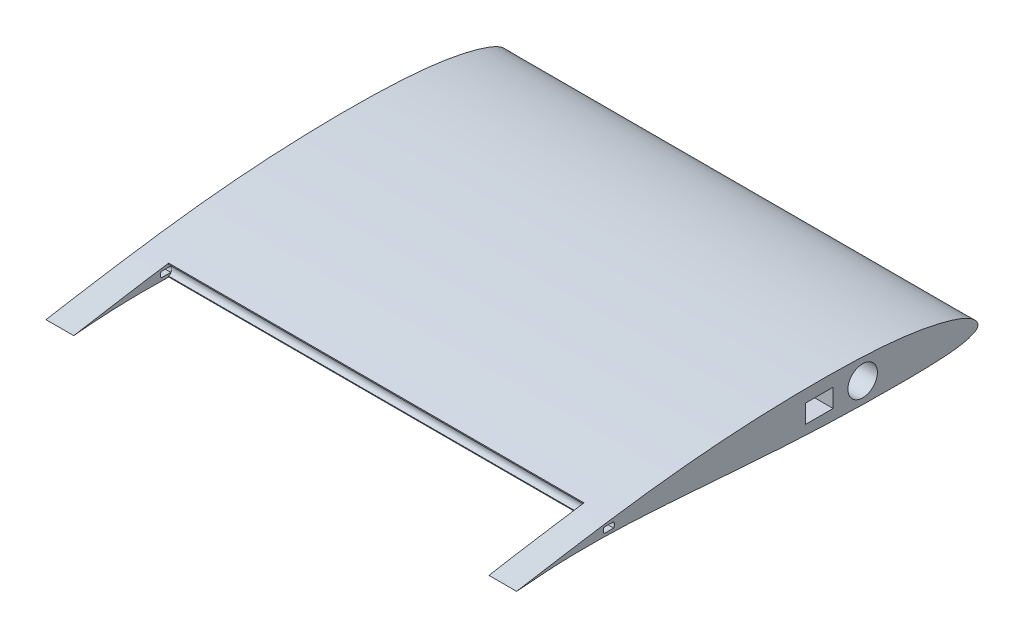
SolidWorks part; units mm, degrees
material "Foam"
ref_plane "Piano frontale" through (0, 0, 0) normal (0, 0, 1) x (1, 0, 0)
ref_plane "Piano superiore" through (0, 0, 0) normal (0, 1, 0) x (1, 0, 0)
ref_plane "Piano destro" through (0, 0, 0) normal (1, 0, 0) x (0, 0, -1)
curve "Curva1"
  spline degree 3 poles (0, 0.1724, 248.285) (0, -0.053, 250.4273) (0, 0.2462, 248.3284) (0, 0.5529, 246.6445) (0, 1.2459, 242.6221) (0, 2.0989, 237.7464) (0, 3.1818, 231.3634) (0, 4.2933, 223.9772) (0, 5.7312, 215.5604) (0, 7.1315, 206.3004) (0, 8.6324, 196.1631) (0, 10.1162, 185.3524) (0, 11.5493, 173.9891) (0, 12.8816, 162.1914) (0, 14.0593, 150.0724) (0, 15.0523, 137.7438) (0, 15.8256, 125.3116) (0, 16.3834, 112.8888) (0, 16.7267, 100.597) (0, 16.8648, 88.5669) (0, 16.792, 76.9314) (0, 16.4941, 65.8165) (0, 15.9609, 55.3329) (0, 15.1594, 45.573) (0, 14.0978, 36.6074) (0, 12.7884, 28.4972) (0, 11.2839, 21.2988) (0, 9.6413, 15.0749) (0, 7.9136, 9.8809) (0, 6.1182, 5.7699) (0, 4.2384, 2.7289) (0, 2.3057, 0.8126) (0, 0.7927, 0.0312) (0, -0.4105, -0.0213) (0, -1.7115, 0.4949) (0, -2.8658, 2.6253) (0, -4.0404, 5.6977) (0, -4.9287, 10.0719) (0, -5.5974, 15.6262) (0, -6.0122, 22.4122) (0, -6.265, 30.3619) (0, -6.3814, 39.3972) (0, -6.3554, 49.3987) (0, -6.2185, 60.2453) (0, -5.9476, 71.8018) (0, -5.5368, 83.9408) (0, -4.9386, 96.5461) (0, -4.1527, 109.5201) (0, -3.2196, 122.7671) (0, -2.1909, 136.1764) (0, -1.148, 149.6158) (0, -0.1602, 162.9314) (0, 0.706, 175.9537) (0, 1.3896, 188.4999) (0, 1.8332, 200.3712) (0, 1.9676, 211.3376) (0, 1.8232, 221.1842) (0, 1.4973, 229.6804) (0, 1.0741, 236.8065) (0, 0.6857, 242.1894) (0, 0.3087, 246.5181) (0, 0.1724, 248.285) (0, -0.053, 250.4273) (0, 0.2462, 248.3284) knots -0.014202 -0.006329 -0.001589 0 0.001576 0.006211 0.01368 0.023764 0.036307 0.051658 0.068045 0.086769 0.107053 0.128647 0.151303 0.174786 0.19886 0.223309 0.247929 0.272522 0.296848 0.320648 0.343669 0.365658 0.3864 0.405741 0.423561 0.439779 0.454311 0.467034 0.477831 0.486643 0.493542 0.498786 0.50271 0.50309 0.505896 0.510322 0.516831 0.525521 0.536535 0.549945 0.565696 0.583577 0.603379 0.624844 0.647727 0.671743 0.696673 0.722357 0.748609 0.77521 0.801891 0.828329 0.854175 0.879074 0.902636 0.924421 0.943939 0.960827 0.974827 0.985798 0.993671 0.998411 1 1.001576 1.006211 1.01368 periodic
sketch "Schizzo1" plane through (0, 0, 0) normal (1, 0, 0) x (0, 0, -1)
  line L0 (-250, 0) -> (0.0001, 0.0174) construction
  line L1 (0.0001, 0.0174) -> (-0.0034, 50.0174) construction
  line L2 (-62.4999, 16.3096) -> (-62.4999, -6.155) construction
  line L3 (-200, 8.0593) -> (-200, 1.7757) construction
  line L4 (-93.4999, 10.0773) -> (-78.4999, 10.0773)
  line L5 (-93.4999, 10.0773) -> (-93.4999, 0.0773)
  line L6 (-93.4999, 0.0773) -> (-78.4999, 0.0773)
  line L7 (-78.4999, 10.0773) -> (-78.4999, 0.0773)
  circle A0 centre (-62.4999, 5.0773) radius 8
  arc A1 (-200, 8.0593) -> (-200, 1.7757) centre (-200, 4.9175) cw
  spline S0 degree 3 poles (-248.3284, 0.2462) (-250.4273, -0.053) (-248.285, 0.1724) (-246.5181, 0.3087) (-242.1894, 0.6857) (-236.8065, 1.0741) (-229.6804, 1.4973) (-221.1842, 1.8232) (-211.3376, 1.9676) (-200.3712, 1.8332) (-188.4999, 1.3896) (-175.9537, 0.706) (-162.9314, -0.1602) (-149.6158, -1.148) (-136.1764, -2.1909) (-122.7671, -3.2196) (-109.5201, -4.1527) (-96.5461, -4.9386) (-83.9408, -5.5368) (-71.8018, -5.9476) (-60.2453, -6.2185) (-49.3987, -6.3554) (-39.3972, -6.3814) (-30.3619, -6.265) (-22.4122, -6.0122) (-15.6262, -5.5974) (-10.0719, -4.9287) (-5.6977, -4.0404) (-2.6253, -2.8658) (-0.4949, -1.7115) (0.0213, -0.4105) (-0.0312, 0.7927) (-0.8126, 2.3057) (-2.7289, 4.2384) (-5.7699, 6.1182) (-9.8809, 7.9136) (-15.0749, 9.6413) (-21.2988, 11.2839) (-28.4972, 12.7884) (-36.6074, 14.0978) (-45.573, 15.1594) (-55.3329, 15.9609) (-65.8165, 16.4941) (-76.9314, 16.792) (-88.5669, 16.8648) (-100.597, 16.7267) (-112.8888, 16.3834) (-125.3116, 15.8256) (-137.7438, 15.0523) (-150.0724, 14.0593) (-162.1914, 12.8816) (-173.9891, 11.5493) (-185.3524, 10.1162) (-196.1631, 8.6324) (-206.3004, 7.1315) (-215.5604, 5.7312) (-223.9772, 4.2933) (-231.3634, 3.1818) (-237.7464, 2.0989) (-242.6221, 1.2459) (-246.6445, 0.5529) (-248.3284, 0.2462) (-250.4273, -0.053) (-248.285, 0.1724) knots -0.01368 -0.006211 -0.001576 0 0.001589 0.006329 0.014202 0.025173 0.039173 0.056061 0.075579 0.097364 0.120926 0.145825 0.171671 0.198109 0.22479 0.251391 0.277643 0.303327 0.328257 0.352273 0.375156 0.396621 0.416423 0.434304 0.450055 0.463465 0.474479 0.483169 0.489678 0.494104 0.49691 0.49729 0.501214 0.506458 0.513357 0.522169 0.532966 0.545689 0.560221 0.576439 0.594259 0.6136 0.634342 0.656331 0.679352 0.703152 0.727478 0.752071 0.776691 0.80114 0.825214 0.848697 0.871353 0.892947 0.913231 0.931955 0.948342 0.963693 0.976236 0.98632 0.993789 0.998424 1 1.001589 1.006329 1.014202 only from (-250, 0) to (-250, 0) construction
  spline S1 degree 3 poles (-200, 1.7757) (-196.2415, 1.6788) (-188.276, 1.3774) (-175.9537, 0.706) (-162.9314, -0.1602) (-149.6158, -1.148) (-136.1764, -2.1909) (-122.7671, -3.2196) (-109.5201, -4.1527) (-96.5461, -4.9386) (-83.9408, -5.5368) (-71.8018, -5.9476) (-60.2453, -6.2185) (-49.3987, -6.3554) (-39.3972, -6.3814) (-30.3619, -6.265) (-22.4122, -6.0122) (-15.6262, -5.5974) (-10.0719, -4.9287) (-5.6977, -4.0404) (-2.6253, -2.8658) (-0.4949, -1.7115) (0.0213, -0.4105) (-0.0312, 0.7927) (-0.8126, 2.3057) (-2.7289, 4.2384) (-5.7699, 6.1182) (-9.8809, 7.9136) (-15.0749, 9.6413) (-21.2988, 11.2839) (-28.4972, 12.7884) (-36.6074, 14.0978) (-45.573, 15.1594) (-55.3329, 15.9609) (-65.8165, 16.4941) (-76.9314, 16.792) (-88.5669, 16.8648) (-100.597, 16.7267) (-112.8888, 16.3834) (-125.3116, 15.8256) (-137.7438, 15.0523) (-150.0724, 14.0593) (-162.1914, 12.8816) (-173.9891, 11.5493) (-185.3524, 10.1162) (-193.973, 8.933) (-198.7936, 8.2355) (-200, 8.0593) knots 0.09869 0.09869 0.09869 0.09869 0.120926 0.145825 0.171671 0.198109 0.22479 0.251391 0.277643 0.303327 0.328257 0.352273 0.375156 0.396621 0.416423 0.434304 0.450055 0.463465 0.474479 0.483169 0.489678 0.494104 0.49691 0.49729 0.501214 0.506458 0.513357 0.522169 0.532966 0.545689 0.560221 0.576439 0.594259 0.6136 0.634342 0.656331 0.679352 0.703152 0.727478 0.752071 0.776691 0.80114 0.825214 0.848697 0.871353 0.892947 0.900158 0.900158 0.900158 0.900158
  point P12 (-78.4999, 5.0773)
  dimension "D3" = 16
  dimension "D1" = 50
  dimension "D2" = 62.5
  dimension "D4" = 15
  dimension "D5" = 10
  dimension "D6" = 16
  dimension "D7" = 50
  dimension "D8" = 6.2836
extrude "CorpoFoam" add sketch "Schizzo1" along normal blind 225
sketch "Schizzo2" plane through (225, 0, 0) normal (1, 0, 0) x (0, 0, -1)
  line L0 (-200, 8.0593) -> (-200, 1.7757) construction
  line L1 (-203.5, 8.2775) -> (-198.5, 8.2775)
  line L2 (-203.5, 8.2775) -> (-203.5, 1.7346)
  line L3 (-203.5, 1.7346) -> (-198.5, 1.7346)
  line L4 (-198.5, 8.2775) -> (-198.5, 1.7346)
  arc A0 (-200, 1.7757) -> (-200, 8.0593) centre (-200, 4.9175) ccw construction
  spline S0 degree 3 poles (-248.3284, 0.2462) (-250.4273, -0.053) (-248.285, 0.1724) (-246.5181, 0.3087) (-242.1894, 0.6857) (-236.8065, 1.0741) (-229.6804, 1.4973) (-221.1842, 1.8232) (-211.3376, 1.9676) (-200.3712, 1.8332) (-188.4999, 1.3896) (-175.9537, 0.706) (-162.9314, -0.1602) (-149.6158, -1.148) (-136.1764, -2.1909) (-122.7671, -3.2196) (-109.5201, -4.1527) (-96.5461, -4.9386) (-83.9408, -5.5368) (-71.8018, -5.9476) (-60.2453, -6.2185) (-49.3987, -6.3554) (-39.3972, -6.3814) (-30.3619, -6.265) (-22.4122, -6.0122) (-15.6262, -5.5974) (-10.0719, -4.9287) (-5.6977, -4.0404) (-2.6253, -2.8658) (-0.4949, -1.7115) (0.0213, -0.4105) (-0.0312, 0.7927) (-0.8126, 2.3057) (-2.7289, 4.2384) (-5.7699, 6.1182) (-9.8809, 7.9136) (-15.0749, 9.6413) (-21.2988, 11.2839) (-28.4972, 12.7884) (-36.6074, 14.0978) (-45.573, 15.1594) (-55.3329, 15.9609) (-65.8165, 16.4941) (-76.9314, 16.792) (-88.5669, 16.8648) (-100.597, 16.7267) (-112.8888, 16.3834) (-125.3116, 15.8256) (-137.7438, 15.0523) (-150.0724, 14.0593) (-162.1914, 12.8816) (-173.9891, 11.5493) (-185.3524, 10.1162) (-196.1631, 8.6324) (-206.3004, 7.1315) (-215.5604, 5.7312) (-223.9772, 4.2933) (-231.3634, 3.1818) (-237.7464, 2.0989) (-242.6221, 1.2459) (-246.6445, 0.5529) (-248.3284, 0.2462) (-250.4273, -0.053) (-248.285, 0.1724) knots -0.01368 -0.006211 -0.001576 0 0.001589 0.006329 0.014202 0.025173 0.039173 0.056061 0.075579 0.097364 0.120926 0.145825 0.171671 0.198109 0.22479 0.251391 0.277643 0.303327 0.328257 0.352273 0.375156 0.396621 0.416423 0.434304 0.450055 0.463465 0.474479 0.483169 0.489678 0.494104 0.49691 0.49729 0.501214 0.506458 0.513357 0.522169 0.532966 0.545689 0.560221 0.576439 0.594259 0.6136 0.634342 0.656331 0.679352 0.703152 0.727478 0.752071 0.776691 0.80114 0.825214 0.848697 0.871353 0.892947 0.913231 0.931955 0.948342 0.963693 0.976236 0.98632 0.993789 0.998424 1 1.001589 1.006329 1.014202 only from (-250, 0) to (-250, 0) construction
  dimension "D1" = 5
  dimension "D2" = 1.5
extrude "SmussoPosteriore" cut sketch "Schizzo2" against normal through all
sketch "Schizzo3" plane through (225, 0, 0) normal (1, 0, 0) x (0, 0, -1)
  line L1 (-93.4999, 10.0773) -> (-78.4999, 10.0773)
  line L2 (-93.4999, 10.0773) -> (-93.4999, 0.0773)
  line L3 (-93.4999, 0.0773) -> (-78.4999, 0.0773)
  line L4 (-78.4999, 10.0773) -> (-78.4999, 0.0773)
  circle A0 centre (-62.4999, 5.0773) radius 8
  circle A1 centre (-62.4999, 5.0773) radius 8 construction
  spline S0 degree 3 poles (-248.3284, 0.2462) (-250.4273, -0.053) (-248.285, 0.1724) (-246.5181, 0.3087) (-242.1894, 0.6857) (-236.8065, 1.0741) (-229.6804, 1.4973) (-221.1842, 1.8232) (-211.3376, 1.9676) (-200.3712, 1.8332) (-188.4999, 1.3896) (-175.9537, 0.706) (-162.9314, -0.1602) (-149.6158, -1.148) (-136.1764, -2.1909) (-122.7671, -3.2196) (-109.5201, -4.1527) (-96.5461, -4.9386) (-83.9408, -5.5368) (-71.8018, -5.9476) (-60.2453, -6.2185) (-49.3987, -6.3554) (-39.3972, -6.3814) (-30.3619, -6.265) (-22.4122, -6.0122) (-15.6262, -5.5974) (-10.0719, -4.9287) (-5.6977, -4.0404) (-2.6253, -2.8658) (-0.4949, -1.7115) (0.0213, -0.4105) (-0.0312, 0.7927) (-0.8126, 2.3057) (-2.7289, 4.2384) (-5.7699, 6.1182) (-9.8809, 7.9136) (-15.0749, 9.6413) (-21.2988, 11.2839) (-28.4972, 12.7884) (-36.6074, 14.0978) (-45.573, 15.1594) (-55.3329, 15.9609) (-65.8165, 16.4941) (-76.9314, 16.792) (-88.5669, 16.8648) (-100.597, 16.7267) (-112.8888, 16.3834) (-125.3116, 15.8256) (-137.7438, 15.0523) (-150.0724, 14.0593) (-162.1914, 12.8816) (-173.9891, 11.5493) (-185.3524, 10.1162) (-196.1631, 8.6324) (-206.3004, 7.1315) (-215.5604, 5.7312) (-223.9772, 4.2933) (-231.3634, 3.1818) (-237.7464, 2.0989) (-242.6221, 1.2459) (-246.6445, 0.5529) (-248.3284, 0.2462) (-250.4273, -0.053) (-248.285, 0.1724) knots -0.01368 -0.006211 -0.001576 0 0.001589 0.006329 0.014202 0.025173 0.039173 0.056061 0.075579 0.097364 0.120926 0.145825 0.171671 0.198109 0.22479 0.251391 0.277643 0.303327 0.328257 0.352273 0.375156 0.396621 0.416423 0.434304 0.450055 0.463465 0.474479 0.483169 0.489678 0.494104 0.49691 0.49729 0.501214 0.506458 0.513357 0.522169 0.532966 0.545689 0.560221 0.576439 0.594259 0.6136 0.634342 0.656331 0.679352 0.703152 0.727478 0.752071 0.776691 0.80114 0.825214 0.848697 0.871353 0.892947 0.913231 0.931955 0.948342 0.963693 0.976236 0.98632 0.993789 0.998424 1 1.001589 1.006329 1.014202 only from (-250, 0) to (-250, 0) construction
  spline S1 degree 3 poles (-248.3284, 0.2462) (-250.4273, -0.053) (-248.285, 0.1724) (-246.5181, 0.3087) (-242.1894, 0.6857) (-236.8065, 1.0741) (-229.6804, 1.4973) (-221.1842, 1.8232) (-211.3376, 1.9676) (-200.3712, 1.8332) (-188.4999, 1.3896) (-175.9537, 0.706) (-162.9314, -0.1602) (-149.6158, -1.148) (-136.1764, -2.1909) (-122.7671, -3.2196) (-109.5201, -4.1527) (-96.5461, -4.9386) (-83.9408, -5.5368) (-71.8018, -5.9476) (-60.2453, -6.2185) (-49.3987, -6.3554) (-39.3972, -6.3814) (-30.3619, -6.265) (-22.4122, -6.0122) (-15.6262, -5.5974) (-10.0719, -4.9287) (-5.6977, -4.0404) (-2.6253, -2.8658) (-0.4949, -1.7115) (0.0213, -0.4105) (-0.0312, 0.7927) (-0.8126, 2.3057) (-2.7289, 4.2384) (-5.7699, 6.1182) (-9.8809, 7.9136) (-15.0749, 9.6413) (-21.2988, 11.2839) (-28.4972, 12.7884) (-36.6074, 14.0978) (-45.573, 15.1594) (-55.3329, 15.9609) (-65.8165, 16.4941) (-76.9314, 16.792) (-88.5669, 16.8648) (-100.597, 16.7267) (-112.8888, 16.3834) (-125.3116, 15.8256) (-137.7438, 15.0523) (-150.0724, 14.0593) (-162.1914, 12.8816) (-173.9891, 11.5493) (-185.3524, 10.1162) (-196.1631, 8.6324) (-206.3004, 7.1315) (-215.5604, 5.7312) (-223.9772, 4.2933) (-231.3634, 3.1818) (-237.7464, 2.0989) (-242.6221, 1.2459) (-246.6445, 0.5529) (-248.3284, 0.2462) (-250.4273, -0.053) (-248.285, 0.1724) knots -0.01368 -0.006211 -0.001576 0 0.001589 0.006329 0.014202 0.025173 0.039173 0.056061 0.075579 0.097364 0.120926 0.145825 0.171671 0.198109 0.22479 0.251391 0.277643 0.303327 0.328257 0.352273 0.375156 0.396621 0.416423 0.434304 0.450055 0.463465 0.474479 0.483169 0.489678 0.494104 0.49691 0.49729 0.501214 0.506458 0.513357 0.522169 0.532966 0.545689 0.560221 0.576439 0.594259 0.6136 0.634342 0.656331 0.679352 0.703152 0.727478 0.752071 0.776691 0.80114 0.825214 0.848697 0.871353 0.892947 0.913231 0.931955 0.948342 0.963693 0.976236 0.98632 0.993789 0.998424 1 1.001589 1.006329 1.014202 only from (-250, 0) to (-250, 0)
extrude "LatoDestro" add sketch "Schizzo3" along normal blind 15
sketch "Schizzo4" plane through (0, 0, 0) normal (-1, 0, 0) x (0, 0, 1)
  line L1 (78.4999, 10.0773) -> (93.4999, 10.0773)
  line L2 (78.4999, 10.0773) -> (78.4999, 0.0773)
  line L3 (78.4999, 0.0773) -> (93.4999, 0.0773)
  line L4 (93.4999, 10.0773) -> (93.4999, 0.0773)
  circle A0 centre (62.4999, 5.0773) radius 8
  circle A1 centre (62.4999, 5.0773) radius 8 construction
  spline S0 degree 3 poles (248.285, 0.1724) (250.4273, -0.053) (248.3284, 0.2462) (246.6445, 0.5529) (242.6221, 1.2459) (237.7464, 2.0989) (231.3634, 3.1818) (223.9772, 4.2933) (215.5604, 5.7312) (206.3004, 7.1315) (196.1631, 8.6324) (185.3524, 10.1162) (173.9891, 11.5493) (162.1914, 12.8816) (150.0724, 14.0593) (137.7438, 15.0523) (125.3116, 15.8256) (112.8888, 16.3834) (100.597, 16.7267) (88.5669, 16.8648) (76.9314, 16.792) (65.8165, 16.4941) (55.3329, 15.9609) (45.573, 15.1594) (36.6074, 14.0978) (28.4972, 12.7884) (21.2988, 11.2839) (15.0749, 9.6413) (9.8809, 7.9136) (5.7699, 6.1182) (2.7289, 4.2384) (0.8126, 2.3057) (0.0312, 0.7927) (-0.0213, -0.4105) (0.4949, -1.7115) (2.6253, -2.8658) (5.6977, -4.0404) (10.0719, -4.9287) (15.6262, -5.5974) (22.4122, -6.0122) (30.3619, -6.265) (39.3972, -6.3814) (49.3987, -6.3554) (60.2453, -6.2185) (71.8018, -5.9476) (83.9408, -5.5368) (96.5461, -4.9386) (109.5201, -4.1527) (122.7671, -3.2196) (136.1764, -2.1909) (149.6158, -1.148) (162.9314, -0.1602) (175.9537, 0.706) (188.4999, 1.3896) (200.3712, 1.8332) (211.3376, 1.9676) (221.1842, 1.8232) (229.6804, 1.4973) (236.8065, 1.0741) (242.1894, 0.6857) (246.5181, 0.3087) (248.285, 0.1724) (250.4273, -0.053) (248.3284, 0.2462) knots -0.014202 -0.006329 -0.001589 0 0.001576 0.006211 0.01368 0.023764 0.036307 0.051658 0.068045 0.086769 0.107053 0.128647 0.151303 0.174786 0.19886 0.223309 0.247929 0.272522 0.296848 0.320648 0.343669 0.365658 0.3864 0.405741 0.423561 0.439779 0.454311 0.467034 0.477831 0.486643 0.493542 0.498786 0.50271 0.50309 0.505896 0.510322 0.516831 0.525521 0.536535 0.549945 0.565696 0.583577 0.603379 0.624844 0.647727 0.671743 0.696673 0.722357 0.748609 0.77521 0.801891 0.828329 0.854175 0.879074 0.902636 0.924421 0.943939 0.960827 0.974827 0.985798 0.993671 0.998411 1 1.001576 1.006211 1.01368 only from (250, 0) to (250, 0) construction
  spline S1 degree 3 poles (248.285, 0.1724) (250.4273, -0.053) (248.3284, 0.2462) (246.6445, 0.5529) (242.6221, 1.2459) (237.7464, 2.0989) (231.3634, 3.1818) (223.9772, 4.2933) (215.5604, 5.7312) (206.3004, 7.1315) (196.1631, 8.6324) (185.3524, 10.1162) (173.9891, 11.5493) (162.1914, 12.8816) (150.0724, 14.0593) (137.7438, 15.0523) (125.3116, 15.8256) (112.8888, 16.3834) (100.597, 16.7267) (88.5669, 16.8648) (76.9314, 16.792) (65.8165, 16.4941) (55.3329, 15.9609) (45.573, 15.1594) (36.6074, 14.0978) (28.4972, 12.7884) (21.2988, 11.2839) (15.0749, 9.6413) (9.8809, 7.9136) (5.7699, 6.1182) (2.7289, 4.2384) (0.8126, 2.3057) (0.0312, 0.7927) (-0.0213, -0.4105) (0.4949, -1.7115) (2.6253, -2.8658) (5.6977, -4.0404) (10.0719, -4.9287) (15.6262, -5.5974) (22.4122, -6.0122) (30.3619, -6.265) (39.3972, -6.3814) (49.3987, -6.3554) (60.2453, -6.2185) (71.8018, -5.9476) (83.9408, -5.5368) (96.5461, -4.9386) (109.5201, -4.1527) (122.7671, -3.2196) (136.1764, -2.1909) (149.6158, -1.148) (162.9314, -0.1602) (175.9537, 0.706) (188.4999, 1.3896) (200.3712, 1.8332) (211.3376, 1.9676) (221.1842, 1.8232) (229.6804, 1.4973) (236.8065, 1.0741) (242.1894, 0.6857) (246.5181, 0.3087) (248.285, 0.1724) (250.4273, -0.053) (248.3284, 0.2462) knots -0.014202 -0.006329 -0.001589 0 0.001576 0.006211 0.01368 0.023764 0.036307 0.051658 0.068045 0.086769 0.107053 0.128647 0.151303 0.174786 0.19886 0.223309 0.247929 0.272522 0.296848 0.320648 0.343669 0.365658 0.3864 0.405741 0.423561 0.439779 0.454311 0.467034 0.477831 0.486643 0.493542 0.498786 0.50271 0.50309 0.505896 0.510322 0.516831 0.525521 0.536535 0.549945 0.565696 0.583577 0.603379 0.624844 0.647727 0.671743 0.696673 0.722357 0.748609 0.77521 0.801891 0.828329 0.854175 0.879074 0.902636 0.924421 0.943939 0.960827 0.974827 0.985798 0.993671 0.998411 1 1.001576 1.006211 1.01368 only from (250, 0) to (250, 0)
extrude "LatoSinistro" add sketch "Schizzo4" along normal blind 15
sketch "Schizzo5" plane through (-15, 0, 0) normal (-1, 0, 0) x (0, 0, 1)
  line L1 (197.4019, 6.4175) -> (202.5981, 6.4175)
  line L3 (197.4019, 3.4175) -> (202.5981, 3.4175)
  circle A0 centre (200, 4.9175) radius 1.5 construction
  arc A1 (197.4019, 6.4175) -> (197.4019, 3.4175) centre (200, 4.9175) ccw
  arc A2 (202.5981, 3.4175) -> (202.5981, 6.4175) centre (200, 4.9175) ccw
  dimension "D1" = 3
  dimension "D2" = 6
extrude "ForoPernoAlettone" cut sketch "Schizzo5" against normal through all
sketch "Schizzo6" plane through (240, 0, 0) normal (1, 0, 0) x (0, 0, -1)
  line L1 (-68.4999, 13.0773) -> (-56.4999, 13.0773)
  line L3 (-68.4999, -2.9227) -> (-56.4999, -2.9227)
  arc A0 (-68.4999, 13.0773) -> (-68.4999, -2.9227) centre (-62.4999, 5.0773) ccw
  circle A1 centre (-62.4999, 5.0773) radius 8 construction
  arc A2 (-56.4999, -2.9227) -> (-56.4999, 13.0773) centre (-62.4999, 5.0773) ccw
  dimension "D1" = 20
extrude "ForoFoamLongherone" cut sketch "Schizzo6" along normal blind 15 from surface at -255 starting at face at (-15, 4.9175, 200)
